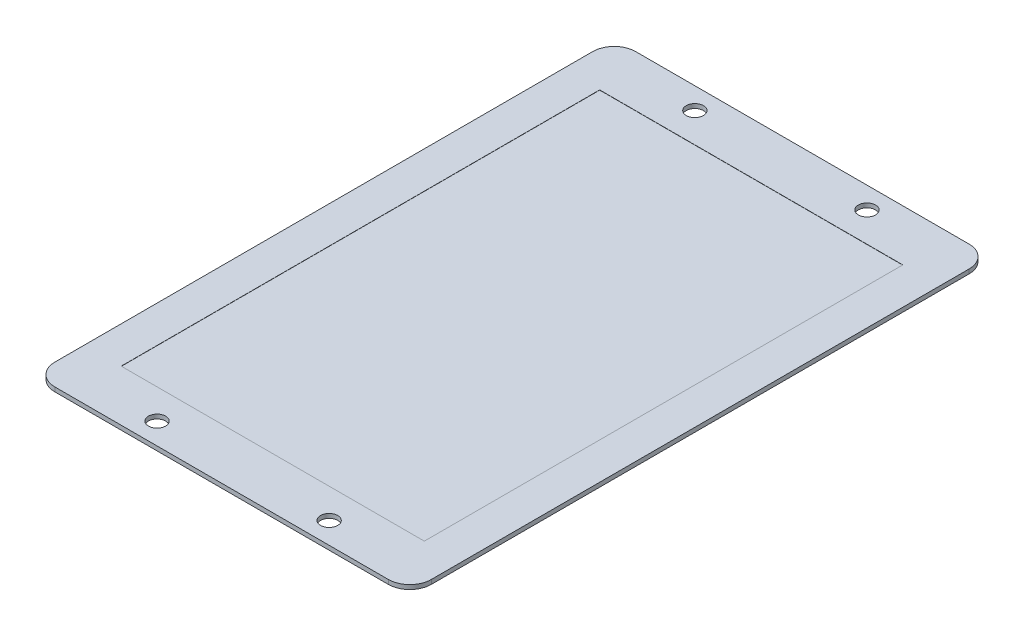
SolidWorks part; units mm, degrees
ref_plane "前视基准面" through (0, 0, 0) normal (0, 0, 1) x (1, 0, 0)
ref_plane "上视基准面" through (0, 0, 0) normal (0, 1, 0) x (1, 0, 0)
ref_plane "右视基准面" through (0, 0, 0) normal (1, 0, 0) x (0, 0, -1)
sketch "草图2" plane through (0, 0, 0) normal (0, 1, 0) x (1, 0, 0)
  line L9 (-87.5, 135) -> (87.5, 135)
  line L10 (-87.5, 135) -> (-87.5, -135)
  line L11 (-87.5, -135) -> (87.5, -135)
  line L12 (87.5, 135) -> (87.5, -135)
  line L13 (-87.5, 135) -> (87.5, -135) construction
  line L14 (-87.5, -135) -> (87.5, 135) construction
  point P0 (0, 0)
  dimension "D1" = 270
  dimension "D2" = 175
extrude "凸台-拉伸1" add sketch "草图2" along normal blind 2
fillet "圆角1" radius 10 4 edges at (87.5, 1, 135) (-87.5, 1, -135) (87.5, 1, -135) (-87.5, 1, 135)
sketch "草图3" plane through (0, 2, 0) normal (0, 1, 0) x (1, 0, 0)
  line L0 (77.5, 135) -> (-77.5, 135) construction
  line L1 (-40, 125) -> (40, 125) construction
  line L2 (-40, 125) -> (-40, -125) construction
  line L3 (-40, -125) -> (40, -125) construction
  line L4 (40, 125) -> (40, -125) construction
  line L5 (-40, 125) -> (40, -125) construction
  line L6 (-40, -125) -> (40, 125) construction
  circle A0 centre (-40, 125) radius 4
  circle A1 centre (40, 125) radius 4
  circle A2 centre (40, -125) radius 4
  circle A3 centre (-40, -125) radius 4
  point P0 (0, 0)
  dimension "D3" = 8
  dimension "D1" = 80
  dimension "D2" = 10
extrude "切除-拉伸1" cut sketch "草图3" against normal through all
sketch "草图4" plane through (0, 2, 0) normal (0, 1, 0) x (1, 0, 0)
  line L1 (-70.4534, 111.2089) -> (70.4534, 111.2089)
  line L2 (-70.4534, 111.2089) -> (-70.4534, -111.2089)
  line L3 (-70.4534, -111.2089) -> (70.4534, -111.2089)
  line L4 (70.4534, 111.2089) -> (70.4534, -111.2089)
  line L5 (-70.4534, 111.2089) -> (70.4534, -111.2089) construction
  line L6 (-70.4534, -111.2089) -> (70.4534, 111.2089) construction
  point P0 (0, 0)
extrude "切除-拉伸2" cut sketch "草图4" against normal blind 0.1
sketch "草图5" plane through (0, 0, 0) normal (0, -1, 0) x (1, 0, 0)
  line L0 (87.5, 125) -> (87.5, -125) construction
  line L1 (42.5, -20) -> (-2.5, -20)
  line L2 (42.5, -20) -> (42.5, 20)
  line L3 (42.5, 20) -> (-2.5, 20)
  line L4 (-2.5, -20) -> (-2.5, 20)
  line L5 (42.5, -20) -> (-2.5, 20) construction
  line L6 (42.5, 20) -> (-2.5, -20) construction
  point P0 (20, 0)
  dimension "D1" = 40
  dimension "D2" = 45
  dimension "D3" = 45
extrude "凸台-拉伸2" add sketch "草图5" along normal blind 15
fillet "圆角2" radius 2 8 edges at (20, -15, 20) (42.5, -15, 0) (20, -15, -20) (-2.5, -15, 0) (42.5, -7.5, 20) (-2.5, -7.5, 20) (42.5, -7.5, -20) (-2.5, -7.5, -20)
